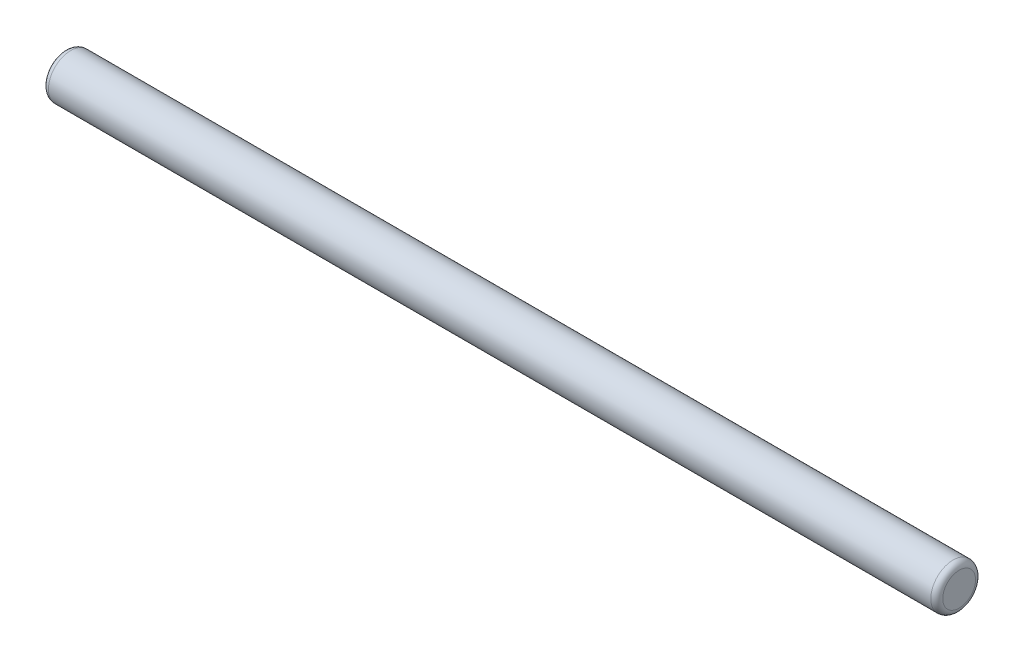
SolidWorks part; units mm, degrees
ref_plane "Front Plane" through (0, 0, 0) normal (0, 0, 1) x (1, 0, 0)
ref_plane "Top Plane" through (0, 0, 0) normal (0, 1, 0) x (1, 0, 0)
ref_plane "Right Plane" through (0, 0, 0) normal (1, 0, 0) x (0, 0, -1)
sketch "Sketch1" plane through (0, 0, 0) normal (1, 0, 0) x (0, 0, -1)
  circle A1 centre (0, 0) radius 0.075
  dimension "D1" = 0.15
extrude "Boss-Extrude1" add sketch "Sketch1" along normal blind 3
fillet "Fillet1" radius 0.02 2 edges at (3, 0, -0.075) (0, 0, -0.075)
